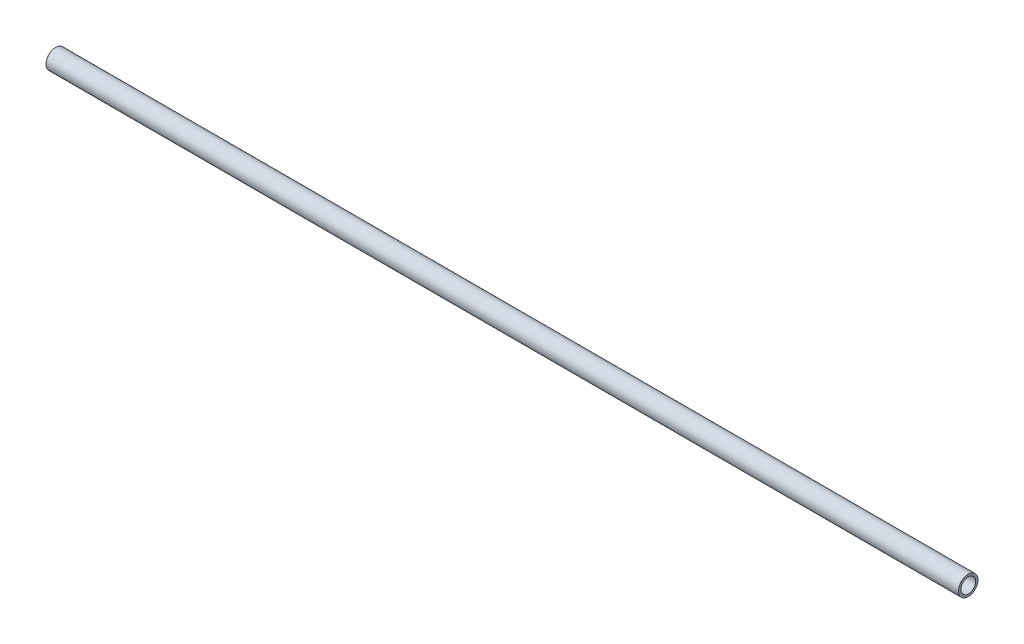
SolidWorks part; units mm, degrees
material "AISI 4130 Steel, annealed at 865C"
ref_plane "Front Plane" through (0, 0, 0) normal (0, 0, 1) x (1, 0, 0)
ref_plane "Top Plane" through (0, 0, 0) normal (0, 1, 0) x (1, 0, 0)
ref_plane "Right Plane" through (0, 0, 0) normal (1, 0, 0) x (0, 0, -1)
sketch "Sketch1" plane through (0, 0, 0) normal (1, 0, 0) x (0, 0, -1)
  circle A0 centre (0, 0) radius 12.7
  circle A1 centre (0, 0) radius 9.652
  dimension "D1" = 25.4
  dimension "D2" = 19.304
extrude "Boss-Extrude1" add sketch "Sketch1" along normal blind 1190
